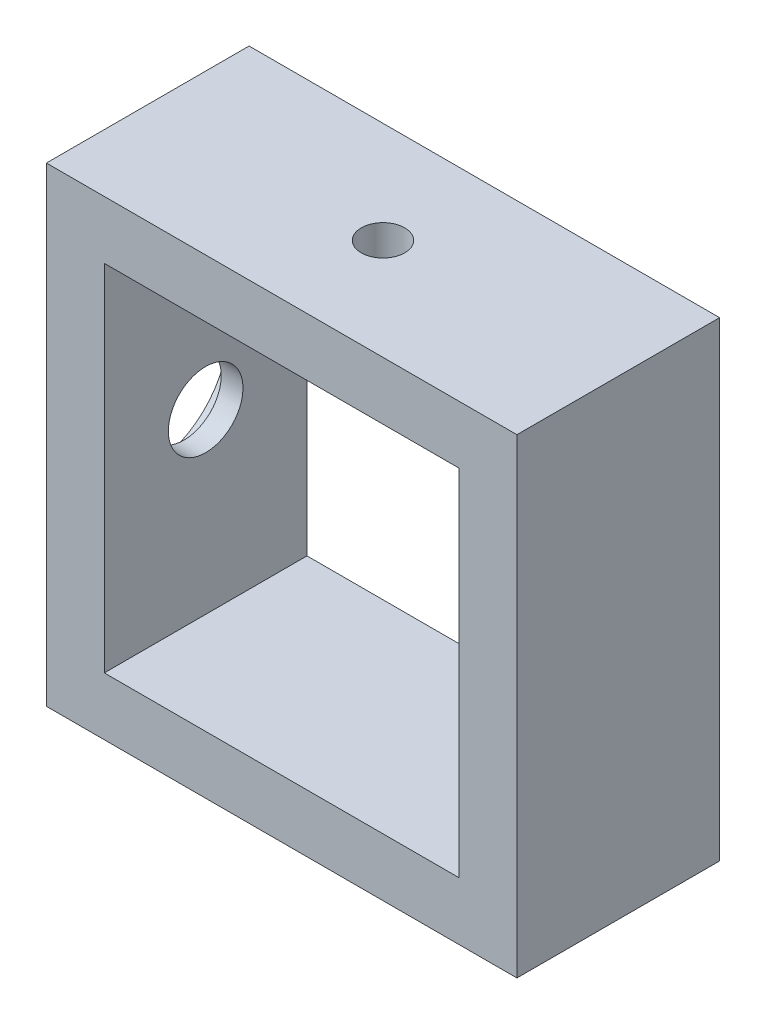
SolidWorks part; units mm, degrees
ref_plane "Alzado" through (0, 0, 0) normal (0, 0, 1) x (1, 0, 0)
ref_plane "Planta" through (0, 0, 0) normal (0, 1, 0) x (1, 0, 0)
ref_plane "Vista lateral" through (0, 0, 0) normal (1, 0, 0) x (0, 0, -1)
sketch "Croquis1" plane through (0, 0, 0) normal (0, 0, 1) x (1, 0, 0)
  line L0 (8, 8) -> (8, 57)
  line L1 (0, 0) -> (65, 0)
  line L2 (0, 0) -> (0, 65)
  line L3 (0, 65) -> (65, 65)
  line L4 (65, 0) -> (65, 65)
  line L5 (8, 57) -> (57, 57)
  line L6 (57, 8) -> (57, 57)
  line L7 (8, 8) -> (57, 8)
  dimension "D1" = 65
  dimension "D2" = 65
  dimension "D3" = 8
extrude "Saliente-Extruir1" add sketch "Croquis1" along normal blind 28
sketch "Croquis2" plane through (0, 0, 0) normal (-1, 0, 0) x (0, 0, 1)
  line L0 (14, 65) -> (14, 0) construction
  line L1 (28, 65) -> (0, 65) construction
  line L2 (28, 0) -> (0, 0) construction
  circle A0 centre (14, 32.5) radius 11.115
extrude "Cortar-Extruir1" cut sketch "Croquis2" against normal blind 5
sketch "Croquis3" plane through (0, 0, 0) normal (-1, 0, 0) x (0, 0, 1)
  line L0 (14, 65) -> (14, 0) construction
  line L1 (28, 65) -> (0, 65) construction
  line L2 (28, 0) -> (0, 0) construction
  circle A0 centre (14, 32.5) radius 5.155
  dimension "D1" = 10.31
extrude "Cortar-Extruir2" cut sketch "Croquis3" against normal blind 8
sketch "Croquis5" plane through (57, 0, 0) normal (-1, 0, 0) x (0, 0, 1)
  line L0 (14, 57) -> (14, 8) construction
  line L1 (28, 57) -> (0, 57) construction
  line L2 (28, 8) -> (0, 8) construction
  circle A0 centre (14, 32.5) radius 6.5
extrude "Cortar-Extruir3" cut sketch "Croquis5" against normal blind 5
sketch "Croquis6" plane through (0, 65, 0) normal (0, 1, 0) x (1, 0, 0)
  line L0 (0, -14) -> (65, -14) construction
  line L1 (0, -28) -> (0, 0) construction
  line L2 (65, -28) -> (65, 0) construction
  circle A0 centre (32.5, -14) radius 3
extrude "Cortar-Extruir4" cut sketch "Croquis6" against normal blind 5 contours A0
sketch "Croquis7" plane through (0, 0, 0) normal (0, -1, 0) x (1, 0, 0)
  line L0 (0, 14) -> (65, 14) construction
  line L1 (0, 28) -> (0, 0) construction
  line L2 (65, 28) -> (65, 0) construction
  circle A0 centre (32.5, 14) radius 3.175
extrude "Cortar-Extruir5" cut sketch "Croquis7" against normal blind 5
